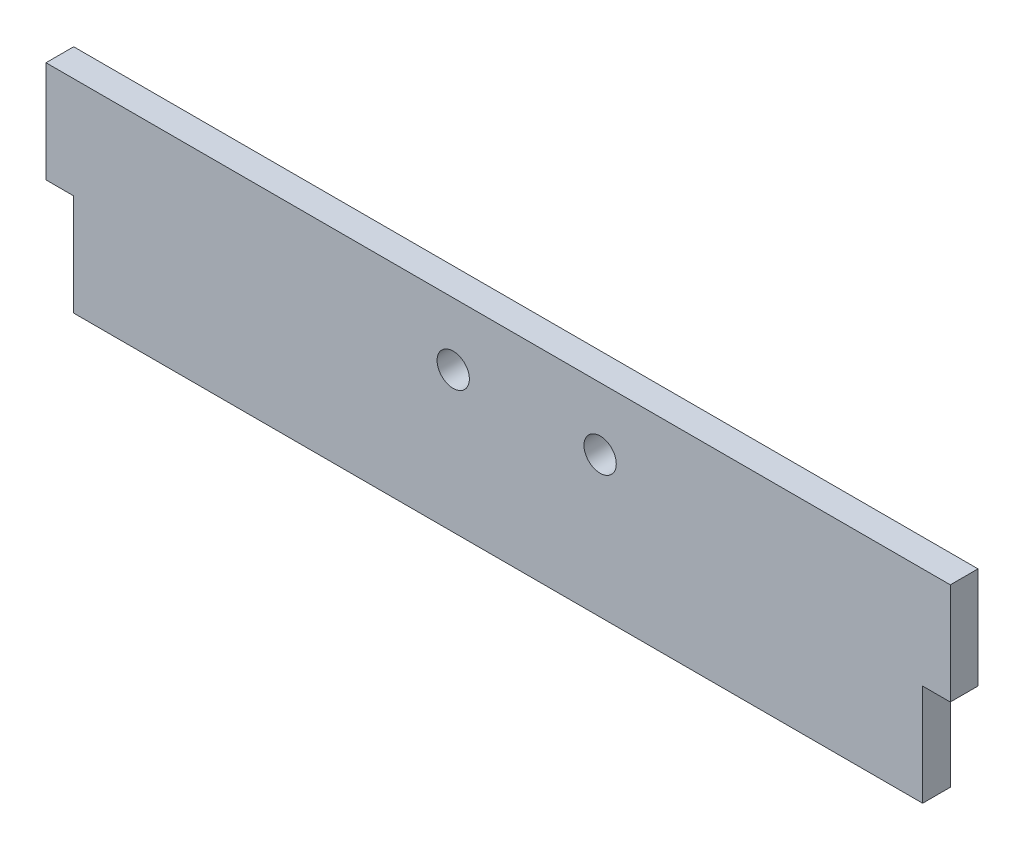
SolidWorks part; units mm, degrees
ref_plane "Front" through (0, 0, 0) normal (0, 0, 1) x (1, 0, 0)
ref_plane "Top" through (0, 0, 0) normal (0, 1, 0) x (1, 0, 0)
ref_plane "Right" through (0, 0, 0) normal (1, 0, 0) x (0, 0, -1)
sketch "Croquis1" plane through (0, 0, 0) normal (0, 0, 1) x (1, 0, 0)
  line L0 (-46, 0) -> (46, 0)
  line L5 (46, 0) -> (46, 11)
  line L6 (46, 11) -> (49, 11)
  line L7 (49, 11) -> (49, 22)
  line L8 (49, 22) -> (-49, 22)
  line L9 (0, 0) -> (0, 22) construction
  line L10 (-49, 11) -> (-49, 22)
  line L11 (-46, 11) -> (-49, 11)
  line L12 (-46, 0) -> (-46, 11)
  dimension "D1" = 3
  dimension "D2" = 11
  dimension "D3" = 11
  dimension "D4" = 46
extrude "Saliente-Extruir1" add sketch "Croquis1" along normal blind 3
sketch "Croquis2" plane through (0, 0, 3) normal (0, 0, 1) x (1, 0, 0)
  line L0 (-4.8703, 16.8237) -> (-4.8703, 13.6752) construction
  line L1 (-4.8703, 15.2495) -> (11.0508, 15.2495) construction
  circle A0 centre (-4.8703, 15.2495) radius 1.75
  circle A1 centre (11.0508, 15.2495) radius 1.75
  dimension "D1" = 3.5
  dimension "D2" = 3.5
extrude "Cortar-Extruir1" cut sketch "Croquis2" against normal blind 3
